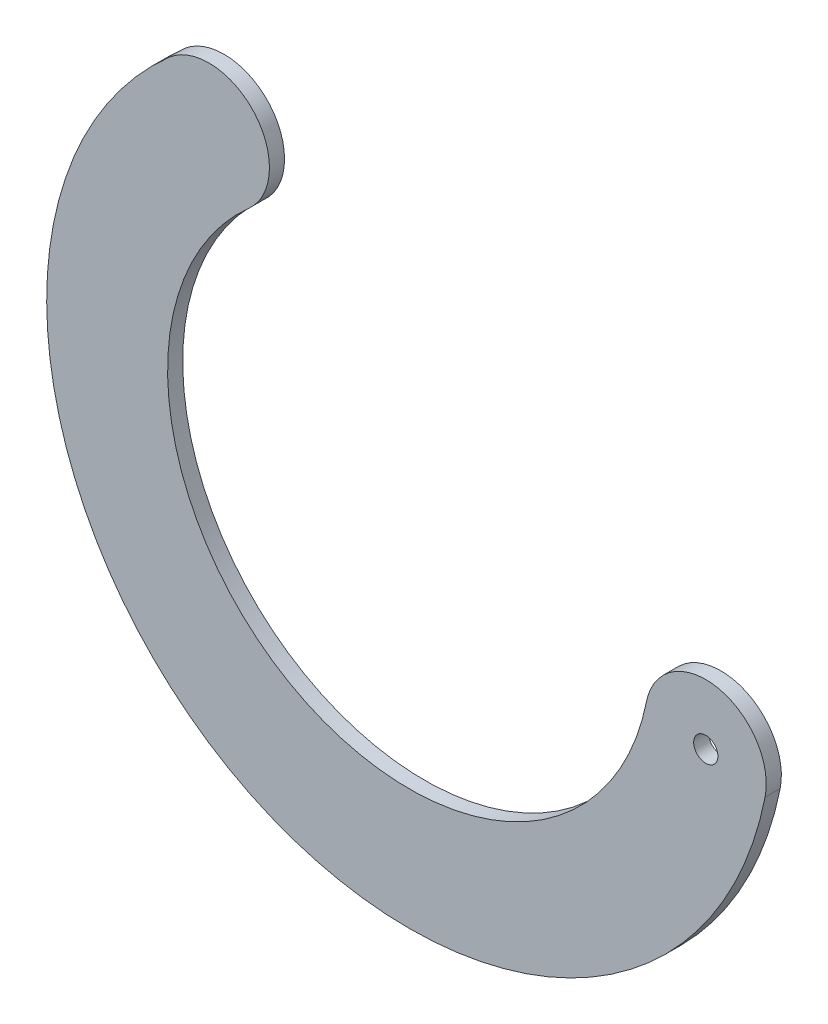
SolidWorks part; units mm, degrees
ref_plane "Front" through (0, 0, 0) normal (0, 0, 1) x (1, 0, 0)
ref_plane "Top" through (0, 0, 0) normal (0, 1, 0) x (1, 0, 0)
ref_plane "Right" through (0, 0, 0) normal (1, 0, 0) x (0, 0, -1)
sketch "Sketch1" plane through (0, 0, 0) normal (0, 0, 1) x (1, 0, 0)
  line L4 (0, 0) -> (0, 56.4661) construction
  line L5 (-32.6007, 56.4661) -> (0, 0) construction
  arc A4 (-50.5285, 57.0378) -> (74.7202, -14.944) centre (0, 0) ccw
  arc A6 (-50.5285, 57.0378) -> (-33.6856, 38.0252) centre (-42.107, 47.5315) cw
  arc A7 (-33.6856, 38.0252) -> (49.8135, -9.9627) centre (0, 0) ccw
  arc A8 (49.8135, -9.9627) -> (74.7202, -14.944) centre (62.2669, -12.4534) cw
  point P5 (64.7575, 0)
  point P30 (-32.6007, 55.9529)
  dimension "D1" = 76.2
  dimension "D2" = 50.8
  dimension "D4" = 12.7
  dimension "D6" = 25.4
  dimension "D5" = 12.7
  dimension "D3" = 30
  dimension "D7" = 25.4
extrude "Boss-Extrude1" add sketch "Sketch1" along normal blind 3.175
hole_wizard "1/4-20 Tapped Hole1" positions "Sketch2" profile "Sketch3" tap size "1/4-20" standard "ANSI Inch" end condition through all
sketch "Sketch2" plane through (0, 0, 3.175) normal (0, 0, 1) x (1, 0, 0)
  point P0 (62.2669, -12.4534)
sketch "Sketch3" plane through (62.2669, -12.4534, 3.175) normal (1, 0, 0) x (0, -1, 0)
  line L0 (0, 0) -> (0, 3.175)
  line L1 (0, 3.175) -> (2.5527, 3.175)
  line L2 (2.5527, 3.175) -> (2.5527, 0)
  line L5 (2.5527, 0) -> (0, 0)
  line L11 (0, -6.35) -> (0, 107.95) construction
  dimension "Thru Tap Drill Dia." = 5.1054
  dimension "Thru Tap Drill Depth" = 3.175
cosmetic thread "Hole Thread1" parameters "D2"=6.35
